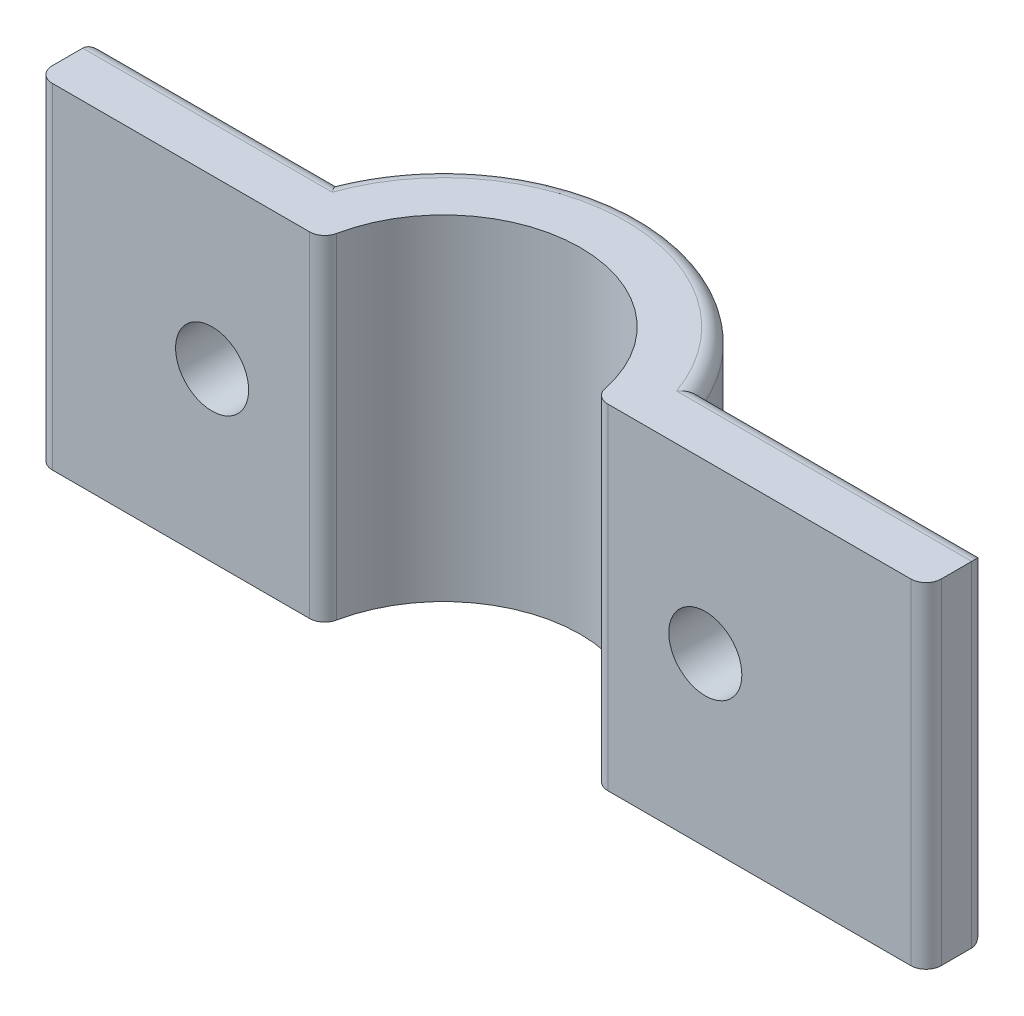
SolidWorks part; units mm, degrees
ref_plane "Front Plane" through (0, 0, 0) normal (0, 0, 1) x (1, 0, 0)
ref_plane "Top Plane" through (0, 0, 0) normal (0, 1, 0) x (1, 0, 0)
ref_plane "Right Plane" through (0, 0, 0) normal (1, 0, 0) x (0, 0, -1)
sketch "Sketch1" plane through (0, 0, 0) normal (0, 1, 0) x (1, 0, 0)
  line L0 (-13.85, 2.5) -> (-6, 2.5)
  line L1 (-6.4807, 0.5) -> (-13.85, 0.5)
  line L2 (-13.85, 2.5) -> (-13.85, 0.5)
  line L3 (6.4807, 0.5) -> (15.35, 0.5)
  line L4 (15.35, 0.5) -> (15.35, 2.5)
  line L5 (-6.4807, 0.5) -> (-4.4721, 0.5)
  line L6 (4.4721, 0.5) -> (6.4807, 0.5)
  line L7 (-6, 2.5) -> (-3.7417, 2.5) construction
  line L8 (-3.7417, 2.5) -> (3.7417, 2.5) construction
  line L9 (3.7417, 2.5) -> (6, 2.5) construction
  line L10 (6, 2.5) -> (15.35, 2.5)
  arc A0 (4.4721, 0.5) -> (-4.4721, 0.5) centre (0, 0) ccw
  arc A1 (6, 2.5) -> (-6, 2.5) centre (0, 0) ccw
  arc A2 (-4.4721, 0.5) -> (4.4721, 0.5) centre (0, 0) ccw construction
  circle A3 centre (0, 0) radius 4.5 construction
  arc A4 (-6.4807, 0.5) -> (6.4807, 0.5) centre (0, 0) ccw construction
  circle A5 centre (0, 0) radius 6.5 construction
  arc A6 (-6, 2.5) -> (-6.4807, 0.5) centre (0, 0) ccw construction
  arc A7 (6.4807, 0.5) -> (6, 2.5) centre (0, 0) ccw construction
  dimension "D1" = 9
  dimension "D6" = 2.5
  dimension "D2" = 9.35
  dimension "D4" = 2
  dimension "D5" = 7.85
  dimension "D3" = 2
extrude "Boss-Extrude1" add sketch "Sketch1" along normal blind 11 contours L10 A1 L0 L2 L1 L5 A0 L6 L3 L4
sketch "Sketch2" plane through (0, 0, -2.5) normal (0, 0, -1) x (-1, 0, 0)
  line L0 (-15.35, 5.5) -> (13.85, 5.5) construction
  line L1 (-15.35, 11) -> (-15.35, 0) construction
  line L2 (13.85, 11) -> (13.85, 0) construction
  line L3 (0, 0) -> (0, 11) construction
  line L4 (6, 11) -> (-6, 11) construction
  circle A0 centre (-8.1, 5.5) radius 1.2
  circle A1 centre (8.1, 5.5) radius 1.2
  dimension "D1" = 2.4
  dimension "D2" = 2.4
  dimension "D3" = 8.1
  dimension "D4" = 8.1
extrude "Cut-Extrude1" cut sketch "Sketch2" against normal up to surface (2 mm away) up to face at (-9.1611, 5.5, -0.5)
fillet "Fillet1" radius 0.5 12 edges at (-13.85, 5.5, -0.5) (-4.4721, 5.5, -0.5) (4.4721, 5.5, -0.5) (15.35, 5.5, -0.5) (-13.85, 5.5, -2.5) (15.35, 5.5, -2.5) (10.675, 11, -2.5) (-9.925, 11, -2.5) (-9.925, 0, -2.5) (10.675, 0, -2.5) (0, 11, -6.5) (0, 0, -6.5)
equation "\"D2@Sketch2\"=\"D1@Sketch2\""
